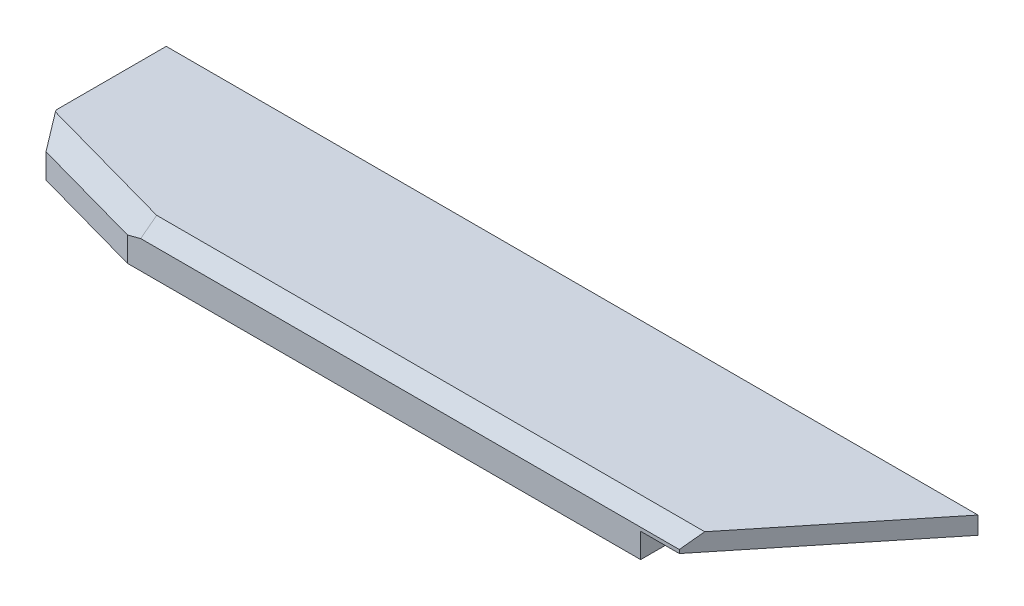
SolidWorks part; units mm, degrees
ref_plane "Front Plane" through (0, 0, 0) normal (0, 0, 1) x (1, 0, 0)
ref_plane "Top Plane" through (0, 0, 0) normal (0, 1, 0) x (1, 0, 0)
ref_plane "Right Plane" through (0, 0, 0) normal (1, 0, 0) x (0, 0, -1)
sketch "Sketch1" plane through (0, 0, 0) normal (0, 1, 0) x (1, 0, 0)
  line L1 (-40.7048, -6.0271) -> (50.2952, -6.0271)
  line L2 (-40.7048, -6.0271) -> (-40.7048, 17.4729)
  line L3 (-40.7048, 17.4729) -> (50.2952, 17.4729)
  line L4 (50.2952, -6.0271) -> (50.2952, 17.4729)
  dimension "D1" = 23.5
  dimension "D2" = 91
extrude "Boss-Extrude1" add sketch "Sketch1" along normal blind 3.5
sketch "Sketch2" plane through (0, 3.5, 0) normal (0, 1, 0) x (1, 0, 0)
  line L0 (-40.7048, 17.4729) -> (-40.7048, -6.0271)
  line L1 (-40.7048, -6.0271) -> (55.7952, -6.0271)
  line L2 (55.7952, -6.0271) -> (74.7952, 17.4729)
  line L3 (74.7952, 17.4729) -> (-40.7048, 17.4729)
  dimension "D1" = 115.5
  dimension "D2" = 96.5
extrude "Boss-Extrude2" add sketch "Sketch2" along normal blind 2.5
chamfer "Chamfer1" distance 5 distance2 18 1 edges at (-40.7048, 3, 6.0271)
chamfer "Chamfer2" distance 2 angle 45 1 edges at (-40.7048, 3, 1.0271)
chamfer "Chamfer3" distance 2.5 angle 45 1 edges at (-30.7413, 6, 3.7948)
chamfer "Chamfer4" distance 2 angle 45 1 edges at (21.2156, 6, 6.0271)
